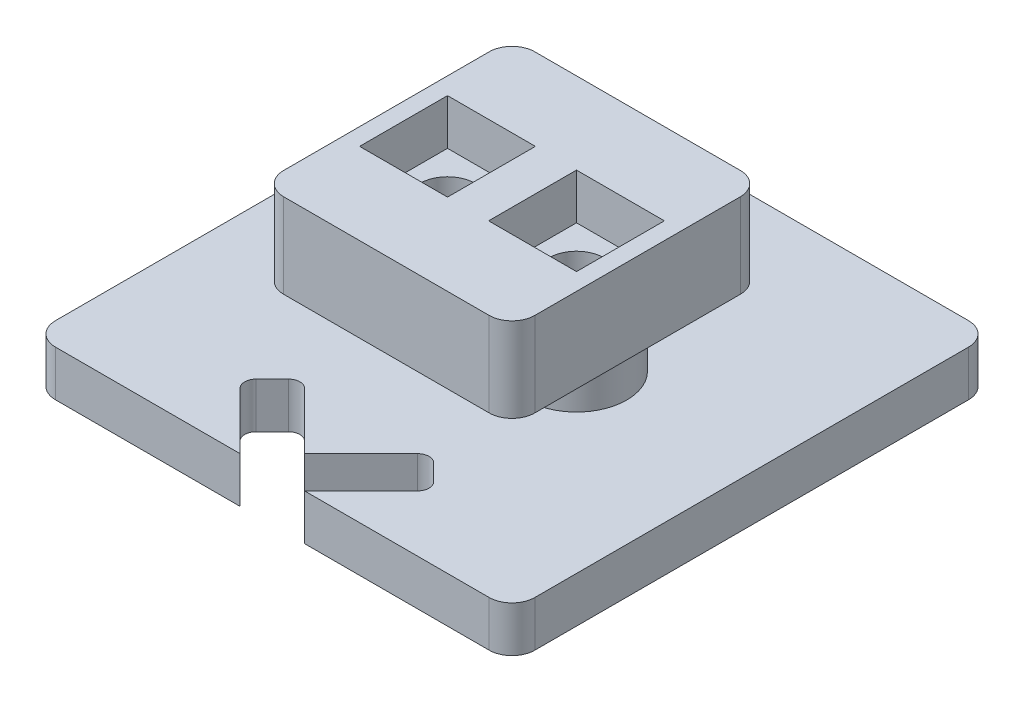
SolidWorks part; units mm, degrees
ref_plane "Front Plane" through (0, 0, 0) normal (0, 0, 1) x (1, 0, 0)
ref_plane "Top Plane" through (0, 0, 0) normal (0, 1, 0) x (1, 0, 0)
ref_plane "Right Plane" through (0, 0, 0) normal (1, 0, 0) x (0, 0, -1)
sketch "Sketch1" plane through (0, 0, 0) normal (0, 1, 0) x (1, 0, 0)
  line L1 (-5.5, -5.5) -> (5.5, -5.5)
  line L2 (-5.5, -5.5) -> (-5.5, 5.5)
  line L3 (-5.5, 5.5) -> (5.5, 5.5)
  line L4 (5.5, -5.5) -> (5.5, 5.5)
  line L5 (-5.5, -5.5) -> (5.5, 5.5) construction
  line L6 (-5.5, 5.5) -> (5.5, -5.5) construction
  point P0 (0, 0)
  dimension "D1" = 11
  dimension "D2" = 11
extrude "Boss-Extrude1" add sketch "Sketch1" along normal blind 3.7
fillet "Fillet1" radius 1 4 edges at (-5.5, 1.85, -5.5) (-5.5, 1.85, 5.5) (5.5, 1.85, -5.5) (5.5, 1.85, 5.5)
sketch "Sketch2" plane through (0, 3.7, 0) normal (0, 1, 0) x (1, 0, 0)
  line L0 (-2.825, 0) -> (2.825, 0) construction
  line L2 (-4.75, -1.925) -> (-0.9, -1.925)
  line L3 (-4.75, -1.925) -> (-4.75, 1.925)
  line L4 (-4.75, 1.925) -> (-0.9, 1.925)
  line L5 (-0.9, -1.925) -> (-0.9, 1.925)
  line L6 (-4.75, -1.925) -> (-0.9, 1.925) construction
  line L7 (-4.75, 1.925) -> (-0.9, -1.925) construction
  line L8 (0.9, -1.925) -> (4.75, -1.925)
  line L9 (0.9, -1.925) -> (0.9, 1.925)
  line L10 (0.9, 1.925) -> (4.75, 1.925)
  line L11 (4.75, -1.925) -> (4.75, 1.925)
  line L12 (0.9, -1.925) -> (4.75, 1.925) construction
  line L13 (0.9, 1.925) -> (4.75, -1.925) construction
  point P4 (0, 0)
  dimension "D1" = 3.85
  dimension "D2" = 3.85
  dimension "D3" = 3.85
  dimension "D4" = 3.85
  dimension "D5" = 5.65
extrude "Cut-Extrude1" cut sketch "Sketch2" against normal blind 2
sketch "Sketch4" plane through (0, 0, 0) normal (0, -1, 0) x (-1, 0, 0)
  line L0 (2.825, 0) -> (-2.825, 0) construction
  circle A0 centre (2.825, 0) radius 2.2
  circle A1 centre (-2.825, 0) radius 2.2
  point P4 (0, 0)
  point P8 (0, 0)
  dimension "D1" = 5.65
  dimension "D2" = 4.4
  dimension "D3" = 4.4
extrude "Boss-Extrude2" add sketch "Sketch4" along normal blind 4
sketch "Sketch5" plane through (0, -4, 0) normal (0, -1, 0) x (-1, 0, 0)
  line L1 (9.5, 10.5) -> (-9.5, 10.5)
  line L2 (10.5, 9.5) -> (10.5, -9.5)
  line L3 (9.5, -10.5) -> (-9.5, -10.5)
  line L4 (-10.5, 9.5) -> (-10.5, -9.5)
  line L5 (10.5, 10.5) -> (-10.5, -10.5) construction
  line L6 (10.5, -10.5) -> (-10.5, 10.5) construction
  arc A0 (10.5, -9.5) -> (9.5, -10.5) centre (9.5, -9.5) cw
  arc A1 (-10.5, -9.5) -> (-9.5, -10.5) centre (-9.5, -9.5) ccw
  arc A2 (-9.5, 10.5) -> (-10.5, 9.5) centre (-9.5, 9.5) ccw
  arc A3 (9.5, 10.5) -> (10.5, 9.5) centre (9.5, 9.5) cw
  point P0 (0, 0)
  dimension "D3" = 1
  dimension "D1" = 21
  dimension "D2" = 21
extrude "Boss-Extrude3" add sketch "Sketch5" against normal blind 2
sketch "Sketch3" plane through (0, 3.7, 0) normal (0, 1, 0) x (1, 0, 0)
  line L0 (-2.825, 0) -> (2.825, 0) construction
  circle A0 centre (-2.825, 0) radius 1.2
  circle A1 centre (2.825, 0) radius 1.2
  point P4 (0, 0)
  point P5 (0, 0)
  point P8 (0, 0)
  dimension "D2" = 2.4
  dimension "D3" = 2.4
  dimension "D1" = 5.65
extrude "Cut-Extrude2" cut sketch "Sketch3" against normal through all
sketch "Sketch7" plane through (0, -2, 0) normal (0, 1, 0) x (1, 0, 0)
  line L0 (9.5, -10.5) -> (-9.5, -10.5) construction
  line L1 (2.8284, -14.7426) -> (4.2426, -13.3284)
  line L2 (2.8284, -14.7426) -> (-3.8891, -8.0251)
  line L3 (-3.8891, -7.318) -> (-3.182, -6.6109)
  line L4 (4.2426, -13.3284) -> (-2.4749, -6.6109)
  line L5 (2.8284, -14.7426) -> (-2.8284, -6.2574) construction
  line L6 (-4.2426, -7.6716) -> (4.2426, -13.3284) construction
  line L8 (-4.2426, -13.3284) -> (-2.8284, -14.7426)
  line L9 (-4.2426, -13.3284) -> (2.4749, -6.6109)
  line L10 (3.182, -6.6109) -> (3.8891, -7.318)
  line L11 (-2.8284, -14.7426) -> (3.8891, -8.0251)
  line L12 (-4.2426, -13.3284) -> (4.2426, -7.6716) construction
  line L13 (2.8284, -6.2574) -> (-2.8284, -14.7426) construction
  arc A0 (-2.4749, -6.6109) -> (-3.182, -6.6109) centre (-2.8284, -6.9645) ccw
  arc A1 (3.8891, -7.318) -> (3.8891, -8.0251) centre (3.5355, -7.6716) cw
  arc A2 (3.182, -6.6109) -> (2.4749, -6.6109) centre (2.8284, -6.9645) ccw
  arc A3 (-3.8891, -7.318) -> (-3.8891, -8.0251) centre (-3.5355, -7.6716) ccw
  point P0 (0, -10.5)
  point P7 (0, -10.5)
  point P12 (-1.4142, -10.5)
  point P13 (1.4142, -10.5)
  line M12 (-9.5, -10.5) -> (9.5, -10.5)
  dimension "D7" = 0.5
  dimension "D8" = 0.5
  dimension "D1" = 2
  dimension "D2" = 45
  dimension "D3" = 2
  dimension "D4" = 45
  dimension "D5" = 4
  dimension "D6" = 4
extrude "Cut-Extrude3" cut sketch "Sketch7" against normal through all contours L10 A2 L9 L4 L11 A1 | L3 A3 L2 L9 L4 A0 | L9 L4 M12
equation "\"D2@Sketch2\"=\"D1@Sketch2\""
equation "\"D3@Sketch2\"=\"D1@Sketch2\""
equation "\"D4@Sketch2\"=\"D1@Sketch2\""
equation "\"D2@Sketch1\"=\"D1@Sketch1\""
equation "\"D3@Sketch3\"=\"D2@Sketch3\""
equation "\"D3@Sketch4\"=\"D2@Sketch4\""
equation "\"D2@Sketch5\"=\"D1@Sketch5\""
equation "\"D3@Sketch7\"=\"D1@Sketch7\""
equation "\"D6@Sketch7\"=\"D5@Sketch7\""
